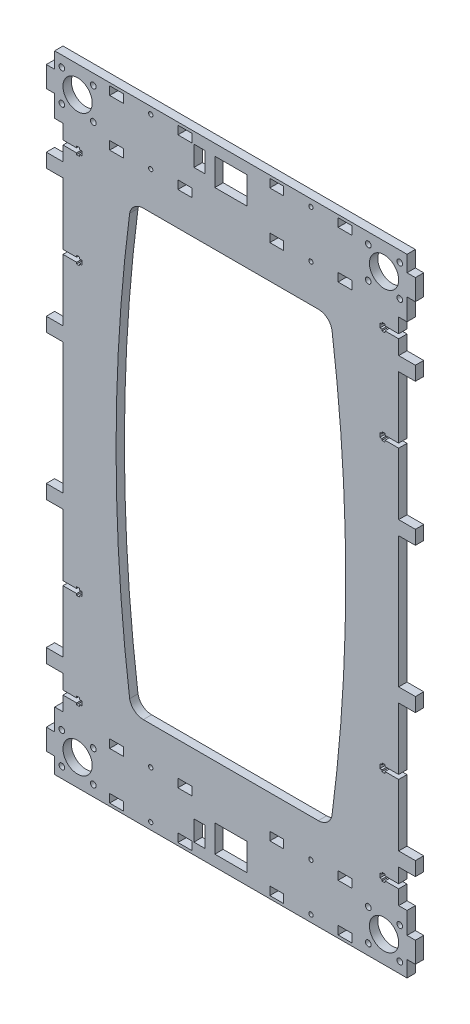
SolidWorks part; units mm, degrees
ref_plane "Front" through (0, 0, 0) normal (0, 0, 1) x (1, 0, 0)
ref_plane "Top" through (0, 0, 0) normal (0, 1, 0) x (1, 0, 0)
ref_plane "Right" through (0, 0, 0) normal (1, 0, 0) x (0, 0, -1)
sketch "Эскиз1" plane through (0, 0, 0) normal (0, 0, 1) x (1, 0, 0)
  line L0 (-38, 217) -> (-38, 223)
  line L1 (-28, 217) -> (-38, 217)
  line L2 (-28, 223) -> (-28, 217)
  line L3 (-38, 223) -> (-28, 223)
  line L4 (-77, 217) -> (-87, 217)
  line L5 (-77, 223) -> (-77, 217)
  line L6 (-87, 223) -> (-77, 223)
  line L7 (-87, 217) -> (-87, 223)
  line L8 (-87, 183) -> (-87, 189)
  line L9 (-77, 183) -> (-87, 183)
  line L10 (-77, 189) -> (-77, 183)
  line L11 (-87, 189) -> (-77, 189)
  line L12 (-28, 189) -> (-28, 183)
  line L13 (-38, 189) -> (-28, 189)
  line L14 (-38, 183) -> (-38, 189)
  line L15 (-28, 183) -> (-38, 183)
  line L16 (28, 223) -> (28, 217)
  line L17 (28, 217) -> (38, 217)
  line L18 (38, 217) -> (38, 223)
  line L19 (38, 223) -> (28, 223)
  line L20 (87, 223) -> (77, 223)
  line L21 (77, 223) -> (77, 217)
  line L22 (77, 217) -> (87, 217)
  line L23 (87, 217) -> (87, 223)
  line L24 (77, 189) -> (77, 183)
  line L25 (77, 183) -> (87, 183)
  line L26 (87, 183) -> (87, 189)
  line L27 (87, 189) -> (77, 189)
  line L28 (38, 183) -> (38, 189)
  line L29 (38, 189) -> (28, 189)
  line L30 (28, 189) -> (28, 183)
  line L31 (28, 183) -> (38, 183)
  line L32 (-120.5, 47) -> (-132.5, 47)
  line L33 (-132.5, 47) -> (-132.5, 57)
  line L34 (-132.5, 57) -> (-120.5, 57)
  line L35 (-120.5, 57) -> (-120.5, 101.45)
  line L36 (-120.5, 101.45) -> (-110.7, 101.45)
  line L37 (-110.7, 101.45) -> (-110.7, 100.25)
  line L38 (-110.7, 100.25) -> (-108.5, 100.25)
  line L39 (-108.5, 100.25) -> (-108.5, 101.45)
  line L40 (-108.5, 101.45) -> (-107, 101.45)
  line L41 (-107, 101.45) -> (-107, 104.55)
  line L42 (-107, 104.55) -> (-108.5, 104.55)
  line L43 (-108.5, 104.55) -> (-108.5, 105.75)
  line L44 (-108.5, 105.75) -> (-110.7, 105.75)
  line L45 (-110.7, 105.75) -> (-110.7, 104.55)
  line L46 (-110.7, 104.55) -> (-120.5, 104.55)
  line L47 (-120.5, 104.55) -> (-120.5, 149)
  line L48 (-120.5, 149) -> (-132.5, 149)
  line L49 (-132.5, 149) -> (-132.5, 159)
  line L50 (-132.5, 159) -> (-120.5, 159)
  line L51 (-120.5, 159) -> (-120.5, 169.45)
  line L52 (-120.5, 169.45) -> (-110.7, 169.45)
  line L53 (-110.7, 169.45) -> (-110.7, 168.25)
  line L54 (-110.7, 168.25) -> (-108.5, 168.25)
  line L55 (-108.5, 168.25) -> (-108.5, 169.45)
  line L56 (-108.5, 169.45) -> (-107, 169.45)
  line L57 (-107, 169.45) -> (-107, 172.55)
  line L58 (-107, 172.55) -> (-108.5, 172.55)
  line L59 (-108.5, 172.55) -> (-108.5, 173.75)
  line L60 (-108.5, 173.75) -> (-110.7, 173.75)
  line L61 (-110.7, 173.75) -> (-110.7, 172.55)
  line L62 (-110.7, 172.55) -> (-120.5, 172.55)
  line L63 (-120.5, 172.55) -> (-120.5, 183)
  line L64 (-120.5, 183) -> (-126.5, 183)
  line L65 (-126.5, 183) -> (-126.5, 198.5)
  line L66 (-126.5, 198.5) -> (-132.5, 198.5)
  line L67 (-132.5, 198.5) -> (-132.5, 213.5)
  line L68 (-132.5, 213.5) -> (-126.5, 213.5)
  line L69 (-126.5, 213.5) -> (-126.5, 225)
  line L70 (126.5, 213.5) -> (126.5, 225)
  line L71 (132.5, 213.5) -> (126.5, 213.5)
  line L72 (132.5, 198.5) -> (132.5, 213.5)
  line L73 (126.5, 198.5) -> (132.5, 198.5)
  line L74 (126.5, 183) -> (126.5, 198.5)
  line L75 (120.5, 183) -> (126.5, 183)
  line L76 (120.5, 172.55) -> (120.5, 183)
  line L77 (110.7, 172.55) -> (120.5, 172.55)
  line L78 (110.7, 173.75) -> (110.7, 172.55)
  line L79 (108.5, 173.75) -> (110.7, 173.75)
  line L80 (108.5, 172.55) -> (108.5, 173.75)
  line L81 (107, 172.55) -> (108.5, 172.55)
  line L82 (107, 169.45) -> (107, 172.55)
  line L83 (108.5, 169.45) -> (107, 169.45)
  line L84 (108.5, 168.25) -> (108.5, 169.45)
  line L85 (110.7, 168.25) -> (108.5, 168.25)
  line L86 (110.7, 169.45) -> (110.7, 168.25)
  line L87 (120.5, 169.45) -> (110.7, 169.45)
  line L88 (120.5, 159) -> (120.5, 169.45)
  line L89 (132.5, 159) -> (120.5, 159)
  line L90 (132.5, 149) -> (132.5, 159)
  line L91 (120.5, 149) -> (132.5, 149)
  line L92 (120.5, 104.55) -> (120.5, 149)
  line L93 (110.7, 104.55) -> (120.5, 104.55)
  line L94 (110.7, 105.75) -> (110.7, 104.55)
  line L95 (108.5, 105.75) -> (110.7, 105.75)
  line L96 (108.5, 104.55) -> (108.5, 105.75)
  line L97 (107, 104.55) -> (108.5, 104.55)
  line L98 (107, 101.45) -> (107, 104.55)
  line L99 (108.5, 101.45) -> (107, 101.45)
  line L100 (108.5, 100.25) -> (108.5, 101.45)
  line L101 (110.7, 100.25) -> (108.5, 100.25)
  line L102 (110.7, 101.45) -> (110.7, 100.25)
  line L103 (120.5, 101.45) -> (110.7, 101.45)
  line L104 (120.5, 57) -> (120.5, 101.45)
  line L105 (132.5, 57) -> (120.5, 57)
  line L106 (132.5, 47) -> (132.5, 57)
  line L107 (120.5, 47) -> (132.5, 47)
  line L108 (-126.5, 225) -> (126.5, 225)
  line L109 (-62.8217, 159) -> (62.8361, 159)
  line L110 (-18.5, 202.5) -> (-18.5, 217)
  line L111 (-18.5, 217) -> (-26.5, 217)
  line L112 (-26.5, 217) -> (-26.5, 202.5)
  line L113 (-26.5, 202.5) -> (-18.5, 202.5)
  line L114 (-11.5, 197.5) -> (-11.5, 217)
  line L115 (11.5, 197.5) -> (11.5, 217)
  line L116 (11.5, 217) -> (-11.5, 217)
  line L117 (-11.5, 197.5) -> (11.5, 197.5)
  line L118 (38, -217) -> (38, -223)
  line L119 (28, -217) -> (38, -217)
  line L120 (28, -223) -> (28, -217)
  line L121 (38, -223) -> (28, -223)
  line L122 (77, -217) -> (87, -217)
  line L123 (77, -223) -> (77, -217)
  line L124 (87, -223) -> (77, -223)
  line L125 (87, -217) -> (87, -223)
  line L126 (87, -183) -> (87, -189)
  line L127 (77, -183) -> (87, -183)
  line L128 (77, -189) -> (77, -183)
  line L129 (87, -189) -> (77, -189)
  line L130 (28, -189) -> (28, -183)
  line L131 (38, -189) -> (28, -189)
  line L132 (38, -183) -> (38, -189)
  line L133 (28, -183) -> (38, -183)
  line L134 (-28, -223) -> (-28, -217)
  line L135 (-28, -217) -> (-38, -217)
  line L136 (-38, -217) -> (-38, -223)
  line L137 (-38, -223) -> (-28, -223)
  line L138 (-87, -223) -> (-77, -223)
  line L139 (-77, -223) -> (-77, -217)
  line L140 (-77, -217) -> (-87, -217)
  line L141 (-87, -217) -> (-87, -223)
  line L142 (-77, -189) -> (-77, -183)
  line L143 (-77, -183) -> (-87, -183)
  line L144 (-87, -183) -> (-87, -189)
  line L145 (-87, -189) -> (-77, -189)
  line L146 (-38, -183) -> (-38, -189)
  line L147 (-38, -189) -> (-28, -189)
  line L148 (-28, -189) -> (-28, -183)
  line L149 (-28, -183) -> (-38, -183)
  line L150 (120.5, -47) -> (132.5, -47)
  line L151 (132.5, -47) -> (132.5, -57)
  line L152 (132.5, -57) -> (120.5, -57)
  line L153 (120.5, -57) -> (120.5, -101.45)
  line L154 (120.5, -101.45) -> (110.7, -101.45)
  line L155 (110.7, -101.45) -> (110.7, -100.25)
  line L156 (110.7, -100.25) -> (108.5, -100.25)
  line L157 (108.5, -100.25) -> (108.5, -101.45)
  line L158 (108.5, -101.45) -> (107, -101.45)
  line L159 (107, -101.45) -> (107, -104.55)
  line L160 (107, -104.55) -> (108.5, -104.55)
  line L161 (108.5, -104.55) -> (108.5, -105.75)
  line L162 (108.5, -105.75) -> (110.7, -105.75)
  line L163 (110.7, -105.75) -> (110.7, -104.55)
  line L164 (110.7, -104.55) -> (120.5, -104.55)
  line L165 (120.5, -104.55) -> (120.5, -149)
  line L166 (120.5, -149) -> (132.5, -149)
  line L167 (132.5, -149) -> (132.5, -159)
  line L168 (132.5, -159) -> (120.5, -159)
  line L169 (120.5, -159) -> (120.5, -169.45)
  line L170 (120.5, -169.45) -> (110.7, -169.45)
  line L171 (110.7, -169.45) -> (110.7, -168.25)
  line L172 (110.7, -168.25) -> (108.5, -168.25)
  line L173 (108.5, -168.25) -> (108.5, -169.45)
  line L174 (108.5, -169.45) -> (107, -169.45)
  line L175 (107, -169.45) -> (107, -172.55)
  line L176 (107, -172.55) -> (108.5, -172.55)
  line L177 (108.5, -172.55) -> (108.5, -173.75)
  line L178 (108.5, -173.75) -> (110.7, -173.75)
  line L179 (110.7, -173.75) -> (110.7, -172.55)
  line L180 (110.7, -172.55) -> (120.5, -172.55)
  line L181 (120.5, -172.55) -> (120.5, -183)
  line L182 (120.5, -183) -> (126.5, -183)
  line L183 (126.5, -183) -> (126.5, -198.5)
  line L184 (126.5, -198.5) -> (132.5, -198.5)
  line L185 (132.5, -198.5) -> (132.5, -213.5)
  line L186 (132.5, -213.5) -> (126.5, -213.5)
  line L187 (126.5, -213.5) -> (126.5, -225)
  line L188 (-126.5, -213.5) -> (-126.5, -225)
  line L189 (-132.5, -213.5) -> (-126.5, -213.5)
  line L190 (-132.5, -198.5) -> (-132.5, -213.5)
  line L191 (-126.5, -198.5) -> (-132.5, -198.5)
  line L192 (-126.5, -183) -> (-126.5, -198.5)
  line L193 (-120.5, -183) -> (-126.5, -183)
  line L194 (-120.5, -172.55) -> (-120.5, -183)
  line L195 (-110.7, -172.55) -> (-120.5, -172.55)
  line L196 (-110.7, -173.75) -> (-110.7, -172.55)
  line L197 (-108.5, -173.75) -> (-110.7, -173.75)
  line L198 (-108.5, -172.55) -> (-108.5, -173.75)
  line L199 (-107, -172.55) -> (-108.5, -172.55)
  line L200 (-107, -169.45) -> (-107, -172.55)
  line L201 (-108.5, -169.45) -> (-107, -169.45)
  line L202 (-108.5, -168.25) -> (-108.5, -169.45)
  line L203 (-110.7, -168.25) -> (-108.5, -168.25)
  line L204 (-110.7, -169.45) -> (-110.7, -168.25)
  line L205 (-120.5, -169.45) -> (-110.7, -169.45)
  line L206 (-120.5, -159) -> (-120.5, -169.45)
  line L207 (-132.5, -159) -> (-120.5, -159)
  line L208 (-132.5, -149) -> (-132.5, -159)
  line L209 (-120.5, -149) -> (-132.5, -149)
  line L210 (-120.5, -104.55) -> (-120.5, -149)
  line L211 (-110.7, -104.55) -> (-120.5, -104.55)
  line L212 (-110.7, -105.75) -> (-110.7, -104.55)
  line L213 (-108.5, -105.75) -> (-110.7, -105.75)
  line L214 (-108.5, -104.55) -> (-108.5, -105.75)
  line L215 (-107, -104.55) -> (-108.5, -104.55)
  line L216 (-107, -101.45) -> (-107, -104.55)
  line L217 (-108.5, -101.45) -> (-107, -101.45)
  line L218 (-108.5, -100.25) -> (-108.5, -101.45)
  line L219 (-110.7, -100.25) -> (-108.5, -100.25)
  line L220 (-110.7, -101.45) -> (-110.7, -100.25)
  line L221 (-120.5, -101.45) -> (-110.7, -101.45)
  line L222 (-120.5, -57) -> (-120.5, -101.45)
  line L223 (-132.5, -57) -> (-120.5, -57)
  line L224 (-132.5, -47) -> (-132.5, -57)
  line L225 (-120.5, -47) -> (-132.5, -47)
  line L226 (126.5, -225) -> (-126.5, -225)
  line L227 (62.8217, -159) -> (-62.8361, -159)
  line L228 (-26.5, -202.5) -> (-26.5, -217)
  line L229 (-26.5, -217) -> (-18.5, -217)
  line L230 (-18.5, -217) -> (-18.5, -202.5)
  line L231 (-18.5, -202.5) -> (-26.5, -202.5)
  line L232 (11.5, -197.5) -> (11.5, -217)
  line L233 (-11.5, -197.5) -> (-11.5, -217)
  line L234 (-11.5, -217) -> (11.5, -217)
  line L235 (11.5, -197.5) -> (-11.5, -197.5)
  line L236 (-120.5, -47) -> (-120.5, 47)
  line L237 (120.5, -47) -> (120.5, 47)
  circle A0 centre (-57.5, 186) radius 1.55
  circle A1 centre (-98.7, 194.7) radius 2.05
  circle A2 centre (-98.7, 217.3) radius 2.05
  circle A3 centre (-110, 206) radius 10.5
  circle A4 centre (-57.5, 220) radius 1.55
  circle A5 centre (-121.3, 217.3) radius 2.05
  circle A6 centre (-121.3, 194.7) radius 2.05
  circle A7 centre (57.5, 186) radius 1.55
  circle A8 centre (98.7, 194.7) radius 2.05
  circle A9 centre (98.7, 217.3) radius 2.05
  circle A10 centre (110, 206) radius 10.5
  circle A11 centre (57.5, 220) radius 1.55
  circle A12 centre (121.3, 217.3) radius 2.05
  circle A13 centre (121.3, 194.7) radius 2.05
  arc A14 (-72.6402, 150.8967) -> (-72.6514, -150.9131) centre (1090.3671, -0.0515) ccw
  arc A15 (-62.8217, 159) -> (-72.6402, 150.8967) centre (-62.8217, 149) ccw
  arc A16 (72.6402, -150.8967) -> (72.6514, 150.9131) centre (-1078.5808, 0.0511) ccw
  arc A17 (72.6514, 150.9131) -> (62.8361, 159) centre (62.8361, 149) ccw
  circle A18 centre (57.5, -186) radius 1.55
  circle A19 centre (98.7, -194.7) radius 2.05
  circle A20 centre (98.7, -217.3) radius 2.05
  circle A21 centre (110, -206) radius 10.5
  circle A22 centre (57.5, -220) radius 1.55
  circle A23 centre (121.3, -217.3) radius 2.05
  circle A24 centre (121.3, -194.7) radius 2.05
  circle A25 centre (-57.5, -186) radius 1.55
  circle A26 centre (-98.7, -194.7) radius 2.05
  circle A27 centre (-98.7, -217.3) radius 2.05
  circle A28 centre (-110, -206) radius 10.5
  circle A29 centre (-57.5, -220) radius 1.55
  circle A30 centre (-121.3, -217.3) radius 2.05
  circle A31 centre (-121.3, -194.7) radius 2.05
  arc A32 (62.8217, -159) -> (72.6402, -150.8967) centre (62.8217, -149) ccw
  arc A33 (-72.6514, -150.9131) -> (-62.8361, -159) centre (-62.8361, -149) ccw
extrude "Бобышка-Вытянуть1" add sketch "Эскиз1" along normal blind 6
